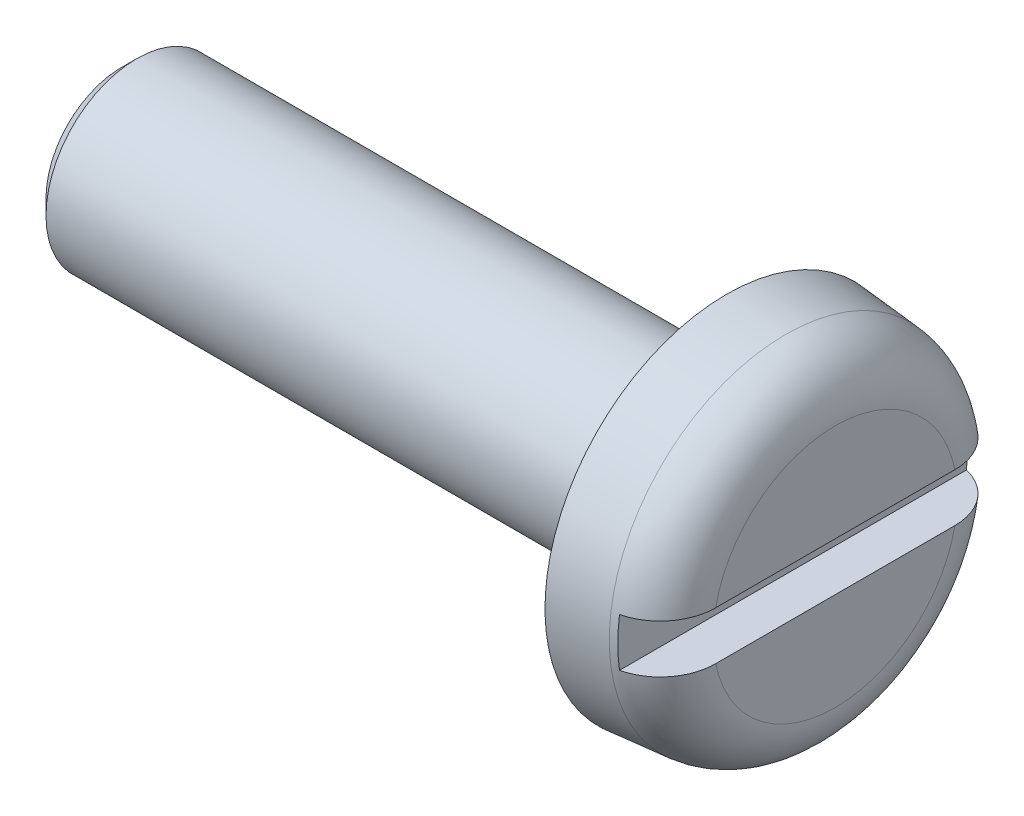
SolidWorks part; units mm, degrees
material "AISI 1020"
ref_plane "Front Plane" through (0, 0, 0) normal (0, 0, 1) x (1, 0, 0)
ref_plane "Top Plane" through (0, 0, 0) normal (0, 1, 0) x (1, 0, 0)
ref_plane "Right Plane" through (0, 0, 0) normal (1, 0, 0) x (0, 0, -1)
sketch "Sketch1" plane through (0, 0, 0) normal (0, 0, 1) x (1, 0, 0)
  line L0 (0, 0) -> (-23.6, 0) construction
  line L1 (0, 0) -> (0, 4.0356)
  line L2 (-1.6431, 5.8288) -> (-3.6, 6)
  line L3 (-3.6, 6) -> (-3.6, 3)
  line L4 (-3.6, 3) -> (-23.6, 3)
  line L5 (-23.6, 3) -> (-23.6, 0)
  line L6 (-23.6, 0) -> (0, 0)
  arc A0 (0, 4.0356) -> (-1.6431, 5.8288) centre (-1.8, 4.0356) ccw
  dimension "G_radius" = 1.8
  dimension "Diam" = 6
  dimension "G_diam" = 12
  dimension "G_plotis" = 3.6
  dimension "G_kampas" = 5
  dimension "Ilgis" = 20
revolve "Revolve1" add sketch "Sketch1" angle 360 about L0
cosmetic thread "Cosmetic Thread1" parameters "Sr_ilgis"=20, "Sr_diam"=5
sketch "Sketch2" plane through (0, 0, 0) normal (1, 0, 0) x (0, 0, -1)
  line L0 (-5.9464, -0.8) -> (5.9464, 0.8) construction
  line L1 (-5.9464, 0.8) -> (5.9464, 0.8)
  line L2 (-5.9464, 0.8) -> (-5.9464, -0.8)
  line L3 (-5.9464, -0.8) -> (5.9464, -0.8)
  line L4 (5.9464, 0.8) -> (5.9464, -0.8)
  circle A0 centre (0, 0) radius 6 construction
  dimension "Y_plotis" = 1.6
extrude "Cut-Extrude1" cut sketch "Sketch2" against normal blind 1.4
chamfer "Chamfer1" distance 0.5 angle 45 1 edges at (-23.6, 3, 0)
